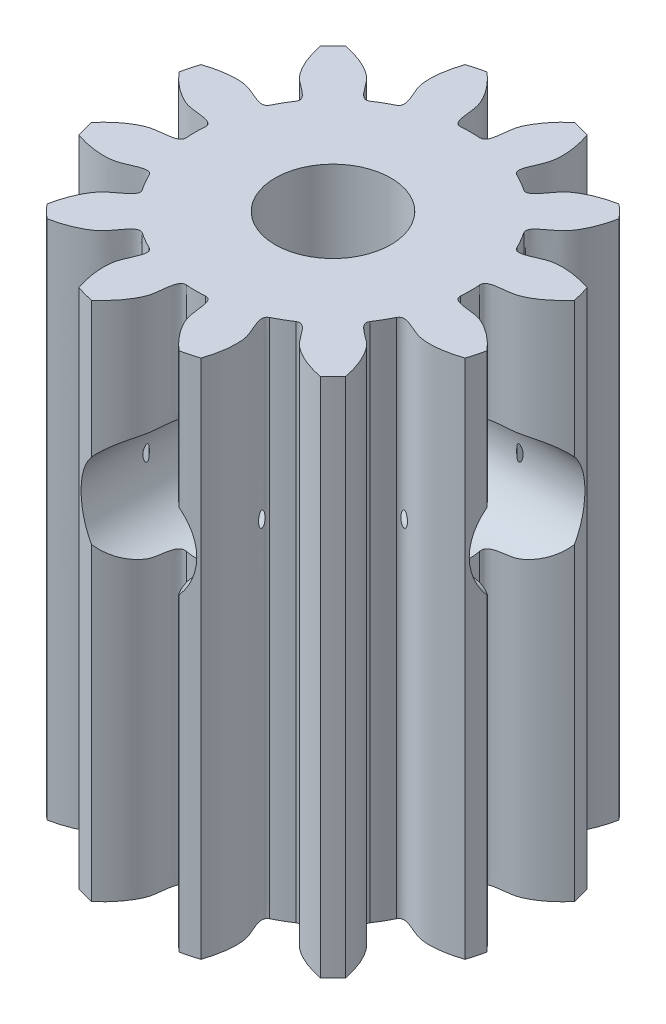
SolidWorks part; units mm, degrees
ref_plane "Front Plane" through (0, 0, 0) normal (0, 0, 1) x (1, 0, 0)
ref_plane "Top Plane" through (0, 0, 0) normal (0, 1, 0) x (1, 0, 0)
ref_plane "Right Plane" through (0, 0, 0) normal (1, 0, 0) x (0, 0, -1)
sketch "12T Module 1 Involute Profile" plane through (0, 0, 0) normal (0, 1, 0) x (1, 0, 0)
  arc A0 (6.8352, 1.5102) -> (6.6745, 2.1097) centre (0, 0) ccw
  arc A1 (4.2693, 2.0823) -> (3.9379, 2.6562) centre (0, 0) ccw
  arc A2 (5.1643, 4.7254) -> (4.7254, 5.1643) centre (0, 0) ccw
  arc A3 (2.6562, 3.9379) -> (2.0823, 4.2693) centre (0, 0) ccw
  arc A4 (2.1097, 6.6745) -> (1.5102, 6.8352) centre (0, 0) ccw
  arc A5 (0.3313, 4.7384) -> (-0.3313, 4.7384) centre (0, 0) ccw
  arc A6 (-1.5102, 6.8352) -> (-2.1097, 6.6745) centre (0, 0) ccw
  arc A7 (-2.0823, 4.2693) -> (-2.6562, 3.9379) centre (0, 0) ccw
  arc A8 (-4.7254, 5.1643) -> (-5.1643, 4.7254) centre (0, 0) ccw
  arc A9 (-3.9379, 2.6562) -> (-4.2693, 2.0823) centre (0, 0) ccw
  arc A10 (-6.6745, 2.1097) -> (-6.8352, 1.5102) centre (0, 0) ccw
  arc A11 (-4.7384, 0.3313) -> (-4.7384, -0.3313) centre (0, 0) ccw
  arc A12 (-6.8352, -1.5102) -> (-6.6745, -2.1097) centre (0, 0) ccw
  arc A13 (-4.2693, -2.0823) -> (-3.9379, -2.6562) centre (0, 0) ccw
  arc A14 (-5.1643, -4.7254) -> (-4.7254, -5.1643) centre (0, 0) ccw
  arc A15 (-2.6562, -3.9379) -> (-2.0823, -4.2693) centre (0, 0) ccw
  arc A16 (-2.1097, -6.6745) -> (-1.5102, -6.8352) centre (0, 0) ccw
  arc A17 (-0.3313, -4.7384) -> (0.3313, -4.7384) centre (0, 0) ccw
  arc A18 (1.5102, -6.8352) -> (2.1097, -6.6745) centre (0, 0) ccw
  arc A19 (2.0823, -4.2693) -> (2.6562, -3.9379) centre (0, 0) ccw
  arc A20 (4.7254, -5.1643) -> (5.1643, -4.7254) centre (0, 0) ccw
  arc A21 (3.9379, -2.6562) -> (4.2693, -2.0823) centre (0, 0) ccw
  arc A22 (6.6745, -2.1097) -> (6.8352, -1.5102) centre (0, 0) ccw
  arc A23 (4.7384, -0.3313) -> (4.7384, 0.3313) centre (0, 0) ccw
  spline S0 degree 3 poles (4.7384, 0.3313) (4.7412, 0.3664) (4.7468, 0.436) (4.8346, 0.5108) (4.9472, 0.554) (5.0847, 0.5831) (5.237, 0.6029) (5.3945, 0.62) (5.5464, 0.6398) (5.655, 0.6626) (5.7231, 0.6847) (5.7602, 0.698) (5.8019, 0.7143) (5.848, 0.7341) (5.8984, 0.7575) (5.9528, 0.7849) (6.011, 0.8166) (6.0729, 0.8527) (6.1383, 0.8935) (6.2067, 0.9394) (6.2782, 0.9904) (6.3523, 1.0469) (6.4287, 1.1091) (6.5073, 1.1771) (6.5877, 1.2511) (6.6696, 1.3314) (6.7529, 1.4179) (6.8073, 1.479) (6.8352, 1.5102) knots 0 0 0 0 0.040341 0.080175 0.128078 0.184595 0.24695 0.311283 0.373476 0.429665 0.443189 0.458849 0.476646 0.49658 0.51865 0.542857 0.569201 0.597681 0.628298 0.661051 0.695942 0.732968 0.772132 0.813432 0.856869 0.902443 0.950153 1 1 1 1
  spline S1 degree 3 poles (4.2693, 2.0823) (4.2892, 2.0533) (4.3288, 1.9958) (4.4423, 1.9749) (4.5614, 1.9938) (4.695, 2.0374) (4.8368, 2.0963) (4.9818, 2.1603) (5.1232, 2.2192) (5.2287, 2.2537) (5.2987, 2.2686) (5.3375, 2.2757) (5.3818, 2.2823) (5.4316, 2.2883) (5.4869, 2.2931) (5.5477, 2.2966) (5.614, 2.2984) (5.6857, 2.298) (5.7627, 2.2953) (5.8449, 2.2898) (5.9323, 2.2813) (6.0247, 2.2694) (6.122, 2.2539) (6.2241, 2.2343) (6.3307, 2.2104) (6.4418, 2.1818) (6.5571, 2.1486) (6.6348, 2.1229) (6.6745, 2.1097) knots 0 0 0 0 0.040341 0.080175 0.128078 0.184595 0.24695 0.311283 0.373476 0.429665 0.443189 0.458849 0.476646 0.49658 0.51865 0.542857 0.569201 0.597681 0.628298 0.661051 0.695942 0.732968 0.772132 0.813432 0.856869 0.902443 0.950153 1 1 1 1
  spline S2 degree 3 poles (3.9379, 2.6562) (3.9228, 2.6879) (3.8929, 2.751) (3.9314, 2.8597) (4.0074, 2.9534) (4.1119, 3.0473) (4.2339, 3.1406) (4.3618, 3.2342) (4.4835, 3.3273) (4.5661, 3.4013) (4.614, 3.4546) (4.6395, 3.4846) (4.6674, 3.5196) (4.6975, 3.5598) (4.7294, 3.6052) (4.7628, 3.6562) (4.7974, 3.7127) (4.833, 3.7749) (4.8691, 3.843) (4.9055, 3.9169) (4.9418, 3.9968) (4.9777, 4.0828) (5.0129, 4.1749) (5.047, 4.2731) (5.0796, 4.3774) (5.1104, 4.4878) (5.1393, 4.6044) (5.1559, 4.6845) (5.1643, 4.7254) knots 0 0 0 0 0.040341 0.080175 0.128078 0.184595 0.24695 0.311283 0.373476 0.429665 0.443189 0.458849 0.476646 0.49658 0.51865 0.542857 0.569201 0.597681 0.628298 0.661051 0.695942 0.732968 0.772132 0.813432 0.856869 0.902443 0.950153 1 1 1 1
  spline S3 degree 3 poles (2.6562, 3.9379) (2.6879, 3.9228) (2.751, 3.8929) (2.8597, 3.9314) (2.9534, 4.0074) (3.0473, 4.1119) (3.1406, 4.2339) (3.2342, 4.3618) (3.3273, 4.4835) (3.4013, 4.5661) (3.4546, 4.614) (3.4846, 4.6395) (3.5196, 4.6674) (3.5598, 4.6975) (3.6052, 4.7294) (3.6562, 4.7628) (3.7127, 4.7974) (3.7749, 4.833) (3.843, 4.8691) (3.9169, 4.9055) (3.9968, 4.9418) (4.0828, 4.9777) (4.1749, 5.0129) (4.2731, 5.047) (4.3774, 5.0796) (4.4878, 5.1104) (4.6044, 5.1393) (4.6845, 5.1559) (4.7254, 5.1643) knots 0 0 0 0 0.040341 0.080175 0.128078 0.184595 0.24695 0.311283 0.373476 0.429665 0.443189 0.458849 0.476646 0.49658 0.51865 0.542857 0.569201 0.597681 0.628298 0.661051 0.695942 0.732968 0.772132 0.813432 0.856869 0.902443 0.950153 1 1 1 1
  spline S4 degree 3 poles (2.0823, 4.2693) (2.0533, 4.2892) (1.9958, 4.3288) (1.9749, 4.4423) (1.9938, 4.5614) (2.0374, 4.695) (2.0963, 4.8368) (2.1603, 4.9818) (2.2192, 5.1232) (2.2537, 5.2287) (2.2686, 5.2987) (2.2757, 5.3375) (2.2823, 5.3818) (2.2883, 5.4316) (2.2931, 5.4869) (2.2966, 5.5477) (2.2984, 5.614) (2.298, 5.6857) (2.2953, 5.7627) (2.2898, 5.8449) (2.2813, 5.9323) (2.2694, 6.0247) (2.2539, 6.122) (2.2343, 6.2241) (2.2104, 6.3307) (2.1818, 6.4418) (2.1486, 6.5571) (2.1229, 6.6348) (2.1097, 6.6745) knots 0 0 0 0 0.040341 0.080175 0.128078 0.184595 0.24695 0.311283 0.373476 0.429665 0.443189 0.458849 0.476646 0.49658 0.51865 0.542857 0.569201 0.597681 0.628298 0.661051 0.695942 0.732968 0.772132 0.813432 0.856869 0.902443 0.950153 1 1 1 1
  spline S5 degree 3 poles (0.3313, 4.7384) (0.3664, 4.7412) (0.436, 4.7468) (0.5108, 4.8346) (0.554, 4.9472) (0.5831, 5.0847) (0.6029, 5.237) (0.62, 5.3945) (0.6398, 5.5464) (0.6626, 5.655) (0.6847, 5.7231) (0.698, 5.7602) (0.7143, 5.8019) (0.7341, 5.848) (0.7575, 5.8984) (0.7849, 5.9528) (0.8166, 6.011) (0.8527, 6.0729) (0.8935, 6.1383) (0.9394, 6.2067) (0.9904, 6.2782) (1.0469, 6.3523) (1.1091, 6.4287) (1.1771, 6.5073) (1.2511, 6.5877) (1.3314, 6.6696) (1.4179, 6.7529) (1.479, 6.8073) (1.5102, 6.8352) knots 0 0 0 0 0.040341 0.080175 0.128078 0.184595 0.24695 0.311283 0.373476 0.429665 0.443189 0.458849 0.476646 0.49658 0.51865 0.542857 0.569201 0.597681 0.628298 0.661051 0.695942 0.732968 0.772132 0.813432 0.856869 0.902443 0.950153 1 1 1 1
  spline S6 degree 3 poles (-0.3313, 4.7384) (-0.3664, 4.7412) (-0.436, 4.7468) (-0.5108, 4.8346) (-0.554, 4.9472) (-0.5831, 5.0847) (-0.6029, 5.237) (-0.62, 5.3945) (-0.6398, 5.5464) (-0.6626, 5.655) (-0.6847, 5.7231) (-0.698, 5.7602) (-0.7143, 5.8019) (-0.7341, 5.848) (-0.7575, 5.8984) (-0.7849, 5.9528) (-0.8166, 6.011) (-0.8527, 6.0729) (-0.8935, 6.1383) (-0.9394, 6.2067) (-0.9904, 6.2782) (-1.0469, 6.3523) (-1.1091, 6.4287) (-1.1771, 6.5073) (-1.2511, 6.5877) (-1.3314, 6.6696) (-1.4179, 6.7529) (-1.479, 6.8073) (-1.5102, 6.8352) knots 0 0 0 0 0.040341 0.080175 0.128078 0.184595 0.24695 0.311283 0.373476 0.429665 0.443189 0.458849 0.476646 0.49658 0.51865 0.542857 0.569201 0.597681 0.628298 0.661051 0.695942 0.732968 0.772132 0.813432 0.856869 0.902443 0.950153 1 1 1 1
  spline S7 degree 3 poles (-2.0823, 4.2693) (-2.0533, 4.2892) (-1.9958, 4.3288) (-1.9749, 4.4423) (-1.9938, 4.5614) (-2.0374, 4.695) (-2.0963, 4.8368) (-2.1603, 4.9818) (-2.2192, 5.1232) (-2.2537, 5.2287) (-2.2686, 5.2987) (-2.2757, 5.3375) (-2.2823, 5.3818) (-2.2883, 5.4316) (-2.2931, 5.4869) (-2.2966, 5.5477) (-2.2984, 5.614) (-2.298, 5.6857) (-2.2953, 5.7627) (-2.2898, 5.8449) (-2.2813, 5.9323) (-2.2694, 6.0247) (-2.2539, 6.122) (-2.2343, 6.2241) (-2.2104, 6.3307) (-2.1818, 6.4418) (-2.1486, 6.5571) (-2.1229, 6.6348) (-2.1097, 6.6745) knots 0 0 0 0 0.040341 0.080175 0.128078 0.184595 0.24695 0.311283 0.373476 0.429665 0.443189 0.458849 0.476646 0.49658 0.51865 0.542857 0.569201 0.597681 0.628298 0.661051 0.695942 0.732968 0.772132 0.813432 0.856869 0.902443 0.950153 1 1 1 1
  spline S8 degree 3 poles (-2.6562, 3.9379) (-2.6879, 3.9228) (-2.751, 3.8929) (-2.8597, 3.9314) (-2.9534, 4.0074) (-3.0473, 4.1119) (-3.1406, 4.2339) (-3.2342, 4.3618) (-3.3273, 4.4835) (-3.4013, 4.5661) (-3.4546, 4.614) (-3.4846, 4.6395) (-3.5196, 4.6674) (-3.5598, 4.6975) (-3.6052, 4.7294) (-3.6562, 4.7628) (-3.7127, 4.7974) (-3.7749, 4.833) (-3.843, 4.8691) (-3.9169, 4.9055) (-3.9968, 4.9418) (-4.0828, 4.9777) (-4.1749, 5.0129) (-4.2731, 5.047) (-4.3774, 5.0796) (-4.4878, 5.1104) (-4.6044, 5.1393) (-4.6845, 5.1559) (-4.7254, 5.1643) knots 0 0 0 0 0.040341 0.080175 0.128078 0.184595 0.24695 0.311283 0.373476 0.429665 0.443189 0.458849 0.476646 0.49658 0.51865 0.542857 0.569201 0.597681 0.628298 0.661051 0.695942 0.732968 0.772132 0.813432 0.856869 0.902443 0.950153 1 1 1 1
  spline S9 degree 3 poles (-3.9379, 2.6562) (-3.9228, 2.6879) (-3.8929, 2.751) (-3.9314, 2.8597) (-4.0074, 2.9534) (-4.1119, 3.0473) (-4.2339, 3.1406) (-4.3618, 3.2342) (-4.4835, 3.3273) (-4.5661, 3.4013) (-4.614, 3.4546) (-4.6395, 3.4846) (-4.6674, 3.5196) (-4.6975, 3.5598) (-4.7294, 3.6052) (-4.7628, 3.6562) (-4.7974, 3.7127) (-4.833, 3.7749) (-4.8691, 3.843) (-4.9055, 3.9169) (-4.9418, 3.9968) (-4.9777, 4.0828) (-5.0129, 4.1749) (-5.047, 4.2731) (-5.0796, 4.3774) (-5.1104, 4.4878) (-5.1393, 4.6044) (-5.1559, 4.6845) (-5.1643, 4.7254) knots 0 0 0 0 0.040341 0.080175 0.128078 0.184595 0.24695 0.311283 0.373476 0.429665 0.443189 0.458849 0.476646 0.49658 0.51865 0.542857 0.569201 0.597681 0.628298 0.661051 0.695942 0.732968 0.772132 0.813432 0.856869 0.902443 0.950153 1 1 1 1
  spline S10 degree 3 poles (-4.2693, 2.0823) (-4.2892, 2.0533) (-4.3288, 1.9958) (-4.4423, 1.9749) (-4.5614, 1.9938) (-4.695, 2.0374) (-4.8368, 2.0963) (-4.9818, 2.1603) (-5.1232, 2.2192) (-5.2287, 2.2537) (-5.2987, 2.2686) (-5.3375, 2.2757) (-5.3818, 2.2823) (-5.4316, 2.2883) (-5.4869, 2.2931) (-5.5477, 2.2966) (-5.614, 2.2984) (-5.6857, 2.298) (-5.7627, 2.2953) (-5.8449, 2.2898) (-5.9323, 2.2813) (-6.0247, 2.2694) (-6.122, 2.2539) (-6.2241, 2.2343) (-6.3307, 2.2104) (-6.4418, 2.1818) (-6.5571, 2.1486) (-6.6348, 2.1229) (-6.6745, 2.1097) knots 0 0 0 0 0.040341 0.080175 0.128078 0.184595 0.24695 0.311283 0.373476 0.429665 0.443189 0.458849 0.476646 0.49658 0.51865 0.542857 0.569201 0.597681 0.628298 0.661051 0.695942 0.732968 0.772132 0.813432 0.856869 0.902443 0.950153 1 1 1 1
  spline S11 degree 3 poles (-4.7384, 0.3313) (-4.7412, 0.3664) (-4.7468, 0.436) (-4.8346, 0.5108) (-4.9472, 0.554) (-5.0847, 0.5831) (-5.237, 0.6029) (-5.3945, 0.62) (-5.5464, 0.6398) (-5.655, 0.6626) (-5.7231, 0.6847) (-5.7602, 0.698) (-5.8019, 0.7143) (-5.848, 0.7341) (-5.8984, 0.7575) (-5.9528, 0.7849) (-6.011, 0.8166) (-6.0729, 0.8527) (-6.1383, 0.8935) (-6.2067, 0.9394) (-6.2782, 0.9904) (-6.3523, 1.0469) (-6.4287, 1.1091) (-6.5073, 1.1771) (-6.5877, 1.2511) (-6.6696, 1.3314) (-6.7529, 1.4179) (-6.8073, 1.479) (-6.8352, 1.5102) knots 0 0 0 0 0.040341 0.080175 0.128078 0.184595 0.24695 0.311283 0.373476 0.429665 0.443189 0.458849 0.476646 0.49658 0.51865 0.542857 0.569201 0.597681 0.628298 0.661051 0.695942 0.732968 0.772132 0.813432 0.856869 0.902443 0.950153 1 1 1 1
  spline S12 degree 3 poles (-4.7384, -0.3313) (-4.7412, -0.3664) (-4.7468, -0.436) (-4.8346, -0.5108) (-4.9472, -0.554) (-5.0847, -0.5831) (-5.237, -0.6029) (-5.3945, -0.62) (-5.5464, -0.6398) (-5.655, -0.6626) (-5.7231, -0.6847) (-5.7602, -0.698) (-5.8019, -0.7143) (-5.848, -0.7341) (-5.8984, -0.7575) (-5.9528, -0.7849) (-6.011, -0.8166) (-6.0729, -0.8527) (-6.1383, -0.8935) (-6.2067, -0.9394) (-6.2782, -0.9904) (-6.3523, -1.0469) (-6.4287, -1.1091) (-6.5073, -1.1771) (-6.5877, -1.2511) (-6.6696, -1.3314) (-6.7529, -1.4179) (-6.8073, -1.479) (-6.8352, -1.5102) knots 0 0 0 0 0.040341 0.080175 0.128078 0.184595 0.24695 0.311283 0.373476 0.429665 0.443189 0.458849 0.476646 0.49658 0.51865 0.542857 0.569201 0.597681 0.628298 0.661051 0.695942 0.732968 0.772132 0.813432 0.856869 0.902443 0.950153 1 1 1 1
  spline S13 degree 3 poles (-4.2693, -2.0823) (-4.2892, -2.0533) (-4.3288, -1.9958) (-4.4423, -1.9749) (-4.5614, -1.9938) (-4.695, -2.0374) (-4.8368, -2.0963) (-4.9818, -2.1603) (-5.1232, -2.2192) (-5.2287, -2.2537) (-5.2987, -2.2686) (-5.3375, -2.2757) (-5.3818, -2.2823) (-5.4316, -2.2883) (-5.4869, -2.2931) (-5.5477, -2.2966) (-5.614, -2.2984) (-5.6857, -2.298) (-5.7627, -2.2953) (-5.8449, -2.2898) (-5.9323, -2.2813) (-6.0247, -2.2694) (-6.122, -2.2539) (-6.2241, -2.2343) (-6.3307, -2.2104) (-6.4418, -2.1818) (-6.5571, -2.1486) (-6.6348, -2.1229) (-6.6745, -2.1097) knots 0 0 0 0 0.040341 0.080175 0.128078 0.184595 0.24695 0.311283 0.373476 0.429665 0.443189 0.458849 0.476646 0.49658 0.51865 0.542857 0.569201 0.597681 0.628298 0.661051 0.695942 0.732968 0.772132 0.813432 0.856869 0.902443 0.950153 1 1 1 1
  spline S14 degree 3 poles (-3.9379, -2.6562) (-3.9228, -2.6879) (-3.8929, -2.751) (-3.9314, -2.8597) (-4.0074, -2.9534) (-4.1119, -3.0473) (-4.2339, -3.1406) (-4.3618, -3.2342) (-4.4835, -3.3273) (-4.5661, -3.4013) (-4.614, -3.4546) (-4.6395, -3.4846) (-4.6674, -3.5196) (-4.6975, -3.5598) (-4.7294, -3.6052) (-4.7628, -3.6562) (-4.7974, -3.7127) (-4.833, -3.7749) (-4.8691, -3.843) (-4.9055, -3.9169) (-4.9418, -3.9968) (-4.9777, -4.0828) (-5.0129, -4.1749) (-5.047, -4.2731) (-5.0796, -4.3774) (-5.1104, -4.4878) (-5.1393, -4.6044) (-5.1559, -4.6845) (-5.1643, -4.7254) knots 0 0 0 0 0.040341 0.080175 0.128078 0.184595 0.24695 0.311283 0.373476 0.429665 0.443189 0.458849 0.476646 0.49658 0.51865 0.542857 0.569201 0.597681 0.628298 0.661051 0.695942 0.732968 0.772132 0.813432 0.856869 0.902443 0.950153 1 1 1 1
  spline S15 degree 3 poles (-2.6562, -3.9379) (-2.6879, -3.9228) (-2.751, -3.8929) (-2.8597, -3.9314) (-2.9534, -4.0074) (-3.0473, -4.1119) (-3.1406, -4.2339) (-3.2342, -4.3618) (-3.3273, -4.4835) (-3.4013, -4.5661) (-3.4546, -4.614) (-3.4846, -4.6395) (-3.5196, -4.6674) (-3.5598, -4.6975) (-3.6052, -4.7294) (-3.6562, -4.7628) (-3.7127, -4.7974) (-3.7749, -4.833) (-3.843, -4.8691) (-3.9169, -4.9055) (-3.9968, -4.9418) (-4.0828, -4.9777) (-4.1749, -5.0129) (-4.2731, -5.047) (-4.3774, -5.0796) (-4.4878, -5.1104) (-4.6044, -5.1393) (-4.6845, -5.1559) (-4.7254, -5.1643) knots 0 0 0 0 0.040341 0.080175 0.128078 0.184595 0.24695 0.311283 0.373476 0.429665 0.443189 0.458849 0.476646 0.49658 0.51865 0.542857 0.569201 0.597681 0.628298 0.661051 0.695942 0.732968 0.772132 0.813432 0.856869 0.902443 0.950153 1 1 1 1
  spline S16 degree 3 poles (-2.0823, -4.2693) (-2.0533, -4.2892) (-1.9958, -4.3288) (-1.9749, -4.4423) (-1.9938, -4.5614) (-2.0374, -4.695) (-2.0963, -4.8368) (-2.1603, -4.9818) (-2.2192, -5.1232) (-2.2537, -5.2287) (-2.2686, -5.2987) (-2.2757, -5.3375) (-2.2823, -5.3818) (-2.2883, -5.4316) (-2.2931, -5.4869) (-2.2966, -5.5477) (-2.2984, -5.614) (-2.298, -5.6857) (-2.2953, -5.7627) (-2.2898, -5.8449) (-2.2813, -5.9323) (-2.2694, -6.0247) (-2.2539, -6.122) (-2.2343, -6.2241) (-2.2104, -6.3307) (-2.1818, -6.4418) (-2.1486, -6.5571) (-2.1229, -6.6348) (-2.1097, -6.6745) knots 0 0 0 0 0.040341 0.080175 0.128078 0.184595 0.24695 0.311283 0.373476 0.429665 0.443189 0.458849 0.476646 0.49658 0.51865 0.542857 0.569201 0.597681 0.628298 0.661051 0.695942 0.732968 0.772132 0.813432 0.856869 0.902443 0.950153 1 1 1 1
  spline S17 degree 3 poles (-0.3313, -4.7384) (-0.3664, -4.7412) (-0.436, -4.7468) (-0.5108, -4.8346) (-0.554, -4.9472) (-0.5831, -5.0847) (-0.6029, -5.237) (-0.62, -5.3945) (-0.6398, -5.5464) (-0.6626, -5.655) (-0.6847, -5.7231) (-0.698, -5.7602) (-0.7143, -5.8019) (-0.7341, -5.848) (-0.7575, -5.8984) (-0.7849, -5.9528) (-0.8166, -6.011) (-0.8527, -6.0729) (-0.8935, -6.1383) (-0.9394, -6.2067) (-0.9904, -6.2782) (-1.0469, -6.3523) (-1.1091, -6.4287) (-1.1771, -6.5073) (-1.2511, -6.5877) (-1.3314, -6.6696) (-1.4179, -6.7529) (-1.479, -6.8073) (-1.5102, -6.8352) knots 0 0 0 0 0.040341 0.080175 0.128078 0.184595 0.24695 0.311283 0.373476 0.429665 0.443189 0.458849 0.476646 0.49658 0.51865 0.542857 0.569201 0.597681 0.628298 0.661051 0.695942 0.732968 0.772132 0.813432 0.856869 0.902443 0.950153 1 1 1 1
  spline S18 degree 3 poles (0.3313, -4.7384) (0.3664, -4.7412) (0.436, -4.7468) (0.5108, -4.8346) (0.554, -4.9472) (0.5831, -5.0847) (0.6029, -5.237) (0.62, -5.3945) (0.6398, -5.5464) (0.6626, -5.655) (0.6847, -5.7231) (0.698, -5.7602) (0.7143, -5.8019) (0.7341, -5.848) (0.7575, -5.8984) (0.7849, -5.9528) (0.8166, -6.011) (0.8527, -6.0729) (0.8935, -6.1383) (0.9394, -6.2067) (0.9904, -6.2782) (1.0469, -6.3523) (1.1091, -6.4287) (1.1771, -6.5073) (1.2511, -6.5877) (1.3314, -6.6696) (1.4179, -6.7529) (1.479, -6.8073) (1.5102, -6.8352) knots 0 0 0 0 0.040341 0.080175 0.128078 0.184595 0.24695 0.311283 0.373476 0.429665 0.443189 0.458849 0.476646 0.49658 0.51865 0.542857 0.569201 0.597681 0.628298 0.661051 0.695942 0.732968 0.772132 0.813432 0.856869 0.902443 0.950153 1 1 1 1
  spline S19 degree 3 poles (2.0823, -4.2693) (2.0533, -4.2892) (1.9958, -4.3288) (1.9749, -4.4423) (1.9938, -4.5614) (2.0374, -4.695) (2.0963, -4.8368) (2.1603, -4.9818) (2.2192, -5.1232) (2.2537, -5.2287) (2.2686, -5.2987) (2.2757, -5.3375) (2.2823, -5.3818) (2.2883, -5.4316) (2.2931, -5.4869) (2.2966, -5.5477) (2.2984, -5.614) (2.298, -5.6857) (2.2953, -5.7627) (2.2898, -5.8449) (2.2813, -5.9323) (2.2694, -6.0247) (2.2539, -6.122) (2.2343, -6.2241) (2.2104, -6.3307) (2.1818, -6.4418) (2.1486, -6.5571) (2.1229, -6.6348) (2.1097, -6.6745) knots 0 0 0 0 0.040341 0.080175 0.128078 0.184595 0.24695 0.311283 0.373476 0.429665 0.443189 0.458849 0.476646 0.49658 0.51865 0.542857 0.569201 0.597681 0.628298 0.661051 0.695942 0.732968 0.772132 0.813432 0.856869 0.902443 0.950153 1 1 1 1
  spline S20 degree 3 poles (2.6562, -3.9379) (2.6879, -3.9228) (2.751, -3.8929) (2.8597, -3.9314) (2.9534, -4.0074) (3.0473, -4.1119) (3.1406, -4.2339) (3.2342, -4.3618) (3.3273, -4.4835) (3.4013, -4.5661) (3.4546, -4.614) (3.4846, -4.6395) (3.5196, -4.6674) (3.5598, -4.6975) (3.6052, -4.7294) (3.6562, -4.7628) (3.7127, -4.7974) (3.7749, -4.833) (3.843, -4.8691) (3.9169, -4.9055) (3.9968, -4.9418) (4.0828, -4.9777) (4.1749, -5.0129) (4.2731, -5.047) (4.3774, -5.0796) (4.4878, -5.1104) (4.6044, -5.1393) (4.6845, -5.1559) (4.7254, -5.1643) knots 0 0 0 0 0.040341 0.080175 0.128078 0.184595 0.24695 0.311283 0.373476 0.429665 0.443189 0.458849 0.476646 0.49658 0.51865 0.542857 0.569201 0.597681 0.628298 0.661051 0.695942 0.732968 0.772132 0.813432 0.856869 0.902443 0.950153 1 1 1 1
  spline S21 degree 3 poles (3.9379, -2.6562) (3.9228, -2.6879) (3.8929, -2.751) (3.9314, -2.8597) (4.0074, -2.9534) (4.1119, -3.0473) (4.2339, -3.1406) (4.3618, -3.2342) (4.4835, -3.3273) (4.5661, -3.4013) (4.614, -3.4546) (4.6395, -3.4846) (4.6674, -3.5196) (4.6975, -3.5598) (4.7294, -3.6052) (4.7628, -3.6562) (4.7974, -3.7127) (4.833, -3.7749) (4.8691, -3.843) (4.9055, -3.9169) (4.9418, -3.9968) (4.9777, -4.0828) (5.0129, -4.1749) (5.047, -4.2731) (5.0796, -4.3774) (5.1104, -4.4878) (5.1393, -4.6044) (5.1559, -4.6845) (5.1643, -4.7254) knots 0 0 0 0 0.040341 0.080175 0.128078 0.184595 0.24695 0.311283 0.373476 0.429665 0.443189 0.458849 0.476646 0.49658 0.51865 0.542857 0.569201 0.597681 0.628298 0.661051 0.695942 0.732968 0.772132 0.813432 0.856869 0.902443 0.950153 1 1 1 1
  spline S22 degree 3 poles (4.2693, -2.0823) (4.2892, -2.0533) (4.3288, -1.9958) (4.4423, -1.9749) (4.5614, -1.9938) (4.695, -2.0374) (4.8368, -2.0963) (4.9818, -2.1603) (5.1232, -2.2192) (5.2287, -2.2537) (5.2987, -2.2686) (5.3375, -2.2757) (5.3818, -2.2823) (5.4316, -2.2883) (5.4869, -2.2931) (5.5477, -2.2966) (5.614, -2.2984) (5.6857, -2.298) (5.7627, -2.2953) (5.8449, -2.2898) (5.9323, -2.2813) (6.0247, -2.2694) (6.122, -2.2539) (6.2241, -2.2343) (6.3307, -2.2104) (6.4418, -2.1818) (6.5571, -2.1486) (6.6348, -2.1229) (6.6745, -2.1097) knots 0 0 0 0 0.040341 0.080175 0.128078 0.184595 0.24695 0.311283 0.373476 0.429665 0.443189 0.458849 0.476646 0.49658 0.51865 0.542857 0.569201 0.597681 0.628298 0.661051 0.695942 0.732968 0.772132 0.813432 0.856869 0.902443 0.950153 1 1 1 1
  spline S23 degree 3 poles (4.7384, -0.3313) (4.7412, -0.3664) (4.7468, -0.436) (4.8346, -0.5108) (4.9472, -0.554) (5.0847, -0.5831) (5.237, -0.6029) (5.3945, -0.62) (5.5464, -0.6398) (5.655, -0.6626) (5.7231, -0.6847) (5.7602, -0.698) (5.8019, -0.7143) (5.848, -0.7341) (5.8984, -0.7575) (5.9528, -0.7849) (6.011, -0.8166) (6.0729, -0.8527) (6.1383, -0.8935) (6.2067, -0.9394) (6.2782, -0.9904) (6.3523, -1.0469) (6.4287, -1.1091) (6.5073, -1.1771) (6.5877, -1.2511) (6.6696, -1.3314) (6.7529, -1.4179) (6.8073, -1.479) (6.8352, -1.5102) knots 0 0 0 0 0.040341 0.080175 0.128078 0.184595 0.24695 0.311283 0.373476 0.429665 0.443189 0.458849 0.476646 0.49658 0.51865 0.542857 0.569201 0.597681 0.628298 0.661051 0.695942 0.732968 0.772132 0.813432 0.856869 0.902443 0.950153 1 1 1 1
extrude "Pinion Tooth Band - 18 mm" add sketch "12T Module 1 Involute Profile" along normal blind 18
sketch "Shaft Bore - 4 mm Through Sketch" plane through (0, 0, 0) normal (0, 1, 0) x (1, 0, 0)
  circle A0 centre (0, 0) radius 2
  dimension "ShaftBoreDiameter" = 4
extrude "Shaft Bore - 4 mm Through" cut sketch "Shaft Bore - 4 mm Through Sketch" along normal through all
sketch "M4 Set Screw Hole 1 - Simplified Sketch" plane through (0, 0, 0) normal (1, 0, 0) x (0, 0, -1)
  circle A0 centre (0, 12) radius 2
  dimension "SetScrewNominalDiameter" = 4
extrude "M4 Set Screw Hole 1 - Simplified" cut sketch "M4 Set Screw Hole 1 - Simplified Sketch" along normal blind 8
sketch "M4 Set Screw Hole 2 - Simplified Sketch" plane through (0, 0, 0) normal (0, 0, 1) x (1, 0, 0)
  circle A0 centre (0, 12) radius 2
  dimension "SetScrewNominalDiameter" = 4
extrude "M4 Set Screw Hole 2 - Simplified" cut sketch "M4 Set Screw Hole 2 - Simplified Sketch" along normal blind 8
